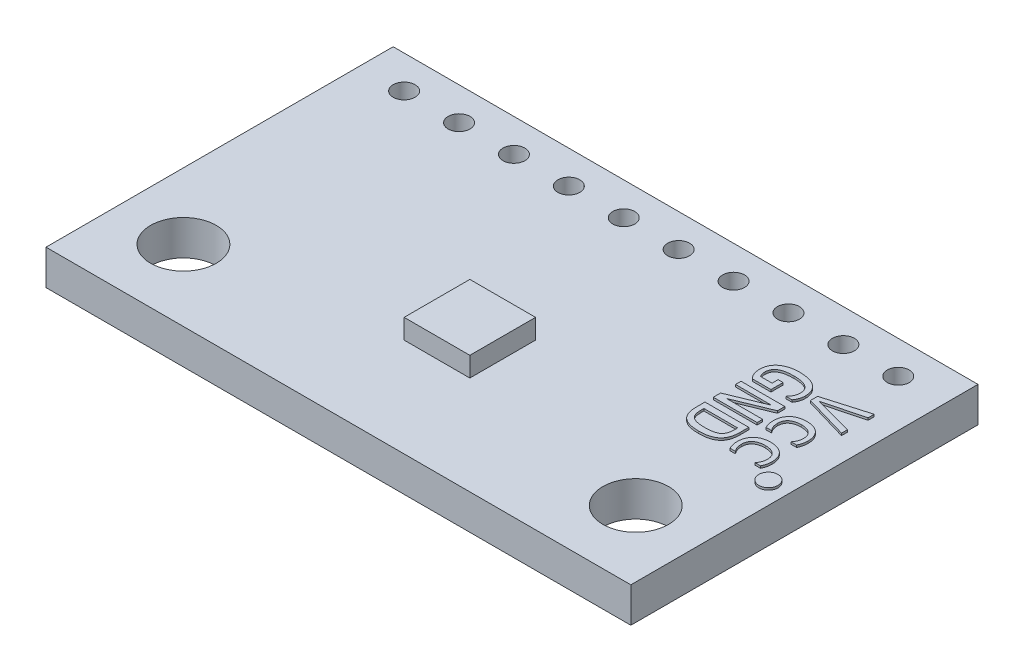
SolidWorks part; units mm, degrees
ref_plane "Front Plane" through (0, 0, 0) normal (0, 0, 1) x (1, 0, 0)
ref_plane "Top Plane" through (0, 0, 0) normal (0, 1, 0) x (1, 0, 0)
ref_plane "Right Plane" through (0, 0, 0) normal (1, 0, 0) x (0, 0, -1)
sketch "Sketch1" plane through (0, 0, 0) normal (0, 1, 0) x (1, 0, 0)
  line L1 (-13.35, 7.925) -> (13.35, 7.925)
  line L2 (-13.35, 7.925) -> (-13.35, -7.925)
  line L3 (-13.35, -7.925) -> (13.35, -7.925)
  line L4 (13.35, 7.925) -> (13.35, -7.925)
  line L5 (-13.35, 7.925) -> (13.35, -7.925) construction
  line L6 (-13.35, -7.925) -> (13.35, 7.925) construction
  point P0 (0, 0)
  dimension "D1" = 26.7
  dimension "D2" = 15.85
extrude "FR4-board" add sketch "Sketch1" along normal blind 1.6
sketch "Sketch2" plane through (0, 1.6, 0) normal (0, 1, 0) x (1, 0, 0)
  line L0 (-13.35, -7.925) -> (13.35, -7.925) construction
  line L1 (-1.5, -0.425) -> (1.5, -0.425)
  line L2 (-1.5, -0.425) -> (-1.5, -3.425)
  line L3 (-1.5, -3.425) -> (1.5, -3.425)
  line L4 (1.5, -0.425) -> (1.5, -3.425)
  line L5 (-1.5, -0.425) -> (1.5, -3.425) construction
  line L6 (-1.5, -3.425) -> (1.5, -0.425) construction
  line L7 (0, 7.925) -> (0, -7.925) construction
  line L8 (13.35, 7.925) -> (-13.35, 7.925) construction
  line L9 (-13.35, 7.925) -> (-13.35, -7.925) construction
  line L10 (13.35, -7.925) -> (13.35, 7.925) construction
  point P0 (0, -1.925)
  dimension "D1" = 3
  dimension "D2" = 3
  dimension "D3" = 4.5
extrude "QFN-chip" add sketch "Sketch2" along normal blind 0.9 separate body
sketch "Sketch4" plane through (0, 0, 0) normal (0, 1, 0) x (1, 0, 0)
  line L0 (-13.35, 6.425) -> (13.35, 6.425) construction
  line L1 (-13.35, 7.925) -> (-13.35, -7.925) construction
  line L2 (13.35, -7.925) -> (13.35, 7.925) construction
  line L3 (13.35, 7.925) -> (-13.35, 7.925) construction
  circle A0 centre (-11.35, 6.425) radius 0.5
  circle A1 centre (-8.8433, 6.425) radius 0.5
  circle A2 centre (-6.3367, 6.425) radius 0.5
  circle A3 centre (-3.83, 6.425) radius 0.5
  circle A4 centre (-1.3233, 6.425) radius 0.5
  circle A5 centre (1.1833, 6.425) radius 0.5
  circle A6 centre (3.69, 6.425) radius 0.5
  circle A7 centre (6.1967, 6.425) radius 0.5
  circle A8 centre (8.7033, 6.425) radius 0.5
  circle A9 centre (11.21, 6.425) radius 0.5
  dimension "D2" = 1
  dimension "D1" = 1.5
  dimension "D3" = 2
  dimension "D4" = 10
extrude "header-connections" cut sketch "Sketch4" along normal through all
sketch "Sketch5" plane through (0, 0, 0) normal (0, 1, 0) x (1, 0, 0)
  line L0 (0, 7.925) -> (0, -7.925) construction
  line L1 (13.35, 7.925) -> (-13.35, 7.925) construction
  line L2 (-13.35, -7.925) -> (13.35, -7.925) construction
  circle A0 centre (-10.325, -4.675) radius 1.5
  circle A1 centre (10.325, -4.675) radius 1.5
  dimension "D1" = 3
  dimension "D3" = 3.25
  dimension "D2" = 20.65
extrude "holes-mounting" cut sketch "Sketch5" along normal through all
sketch "Sketch6" plane through (0, 1.6, 0) normal (0, 1, 0) x (1, 0, 0)
  line L0 (10.2626, 4.3504) -> (10.2626, 0.128) construction
  line L1 (7.9162, 4.3624) -> (7.9162, 0) construction
  circle A0 centre (12.4422, -0.7359) radius 0.4361
  text T0 "Vcc" font "DejaVu Sans Mono" height 2
  text T1 "GND" font "DejaVu Sans Mono" height 2
extrude "Boss-Extrude1" add sketch "Sketch6" along normal blind 0.1
